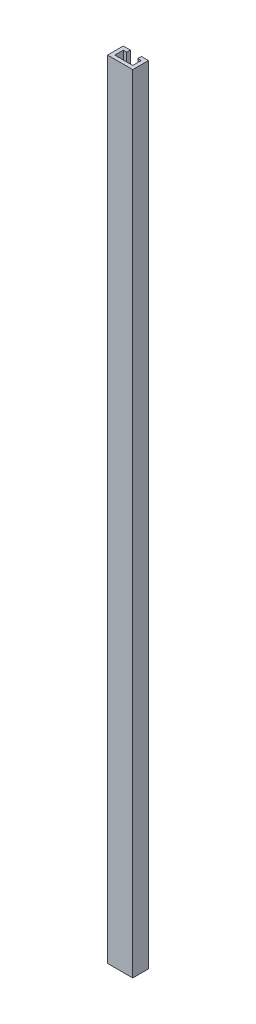
SolidWorks part; units mm, degrees
ref_plane "前视基准面" through (0, 0, 0) normal (0, 0, 1) x (1, 0, 0)
ref_plane "上视基准面" through (0, 0, 0) normal (0, 1, 0) x (1, 0, 0)
ref_plane "右视基准面" through (0, 0, 0) normal (1, 0, 0) x (0, 0, -1)
sketch "草图1" plane through (0, 0, 0) normal (0, 1, 0) x (1, 0, 0)
  line L0 (0, -5) -> (8, -5)
  line L1 (8, -5) -> (8, 0)
  line L2 (8, 0) -> (5.75, 0)
  line L3 (5.75, 0) -> (5.75, -1.15)
  line L4 (5.75, -1.15) -> (6.85, -1.15)
  line L5 (6.85, -1.15) -> (6.85, -3.85)
  line L6 (6.85, -3.85) -> (1.15, -3.85)
  line L7 (1.15, -3.85) -> (1.15, -1.15)
  line L8 (1.15, -1.15) -> (2.25, -1.15)
  line L9 (2.25, -1.15) -> (2.25, 0)
  line L10 (2.25, 0) -> (0, 0)
  line L11 (0, 0) -> (0, -5)
  line L12 (4, -3.85) -> (4, -5) construction
  line L13 (2.25, 0) -> (5.75, 0) construction
  line L14 (4, 0) -> (4, -3.85) construction
  dimension "D1" = 5
  dimension "D2" = 8
  dimension "D3" = 1.15
  dimension "D4" = 1.15
  dimension "D5" = 1.15
  dimension "D6" = 3.5
  dimension "D7" = 5.7
extrude "凸台-拉伸1" add sketch "草图1" along normal blind 250
